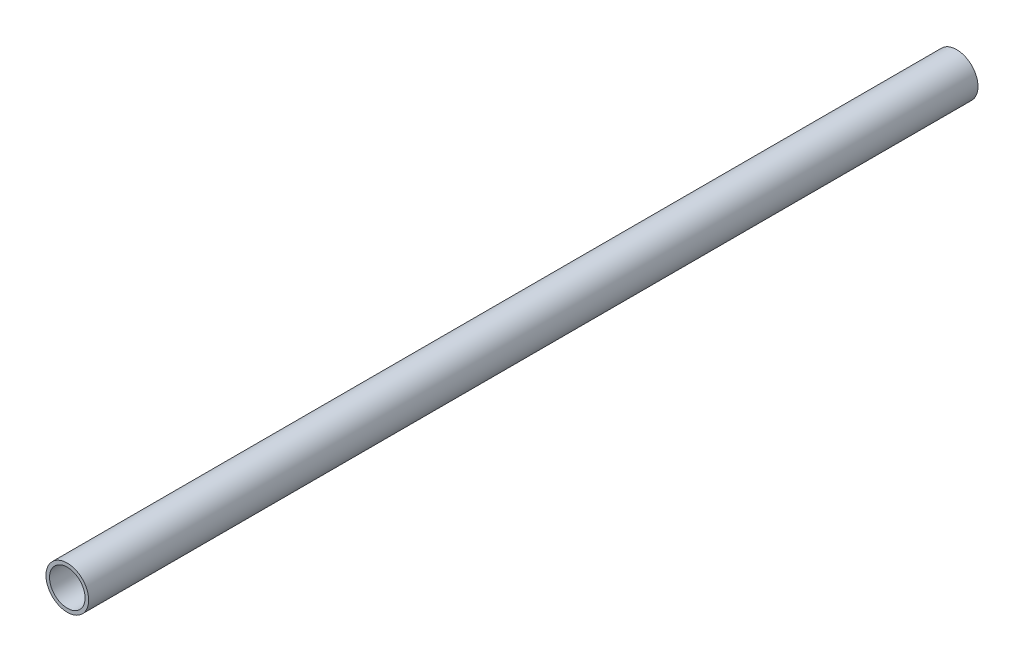
SolidWorks part; units mm, degrees
ref_plane "Front Plane" through (0, 0, 0) normal (0, 0, 1) x (1, 0, 0)
ref_plane "Top Plane" through (0, 0, 0) normal (0, 1, 0) x (1, 0, 0)
ref_plane "Right Plane" through (0, 0, 0) normal (1, 0, 0) x (0, 0, -1)
sketch "Sketch1" plane through (0, 0, 0) normal (0, 0, 1) x (1, 0, 0)
  circle A0 centre (0, 0) radius 6
  circle A1 centre (0, 0) radius 5
  dimension "D1" = 12
  dimension "D2" = 10
extrude "Boss-Extrude1" add sketch "Sketch1" along normal blind 250
